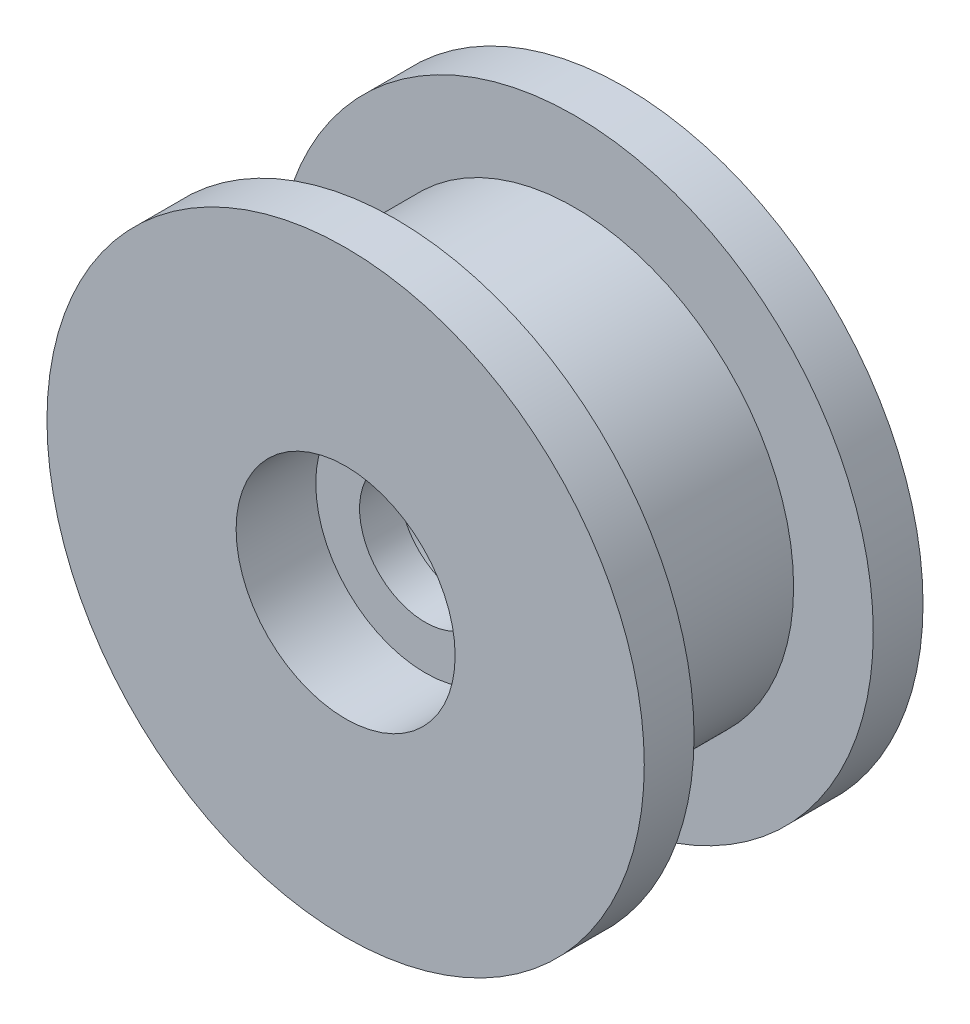
SolidWorks part; units mm, degrees
ref_plane "Front Plane" through (0, 0, 0) normal (0, 0, 1) x (1, 0, 0)
ref_plane "Top Plane" through (0, 0, 0) normal (0, 1, 0) x (1, 0, 0)
ref_plane "Right Plane" through (0, 0, 0) normal (1, 0, 0) x (0, 0, -1)
sketch "Sketch1" plane through (0, 0, 0) normal (0, 1, 0) x (1, 0, 0)
  line L0 (0, 0) -> (0, 21.2409) construction
  line L1 (1.65, 0) -> (7.5, 0)
  line L2 (7.5, 0) -> (7.5, 1.25)
  line L3 (7.5, 1.25) -> (5.5, 1.25)
  line L5 (3, 9) -> (2.75, 9)
  line L6 (2.75, 9) -> (2.75, 3)
  line L7 (2.75, 3) -> (1.65, 3)
  line L8 (1.65, 3) -> (1.65, 0)
  line L12 (3, 7) -> (3, 9)
  line L13 (3, 7) -> (7.5, 7)
  line L14 (7.5, 7) -> (7.5, 5.75)
  line L15 (7.5, 5.75) -> (5.5, 5.75)
  line L16 (5.5, 5.75) -> (5.5, 1.25)
  dimension "D1" = 3.3
  dimension "D2" = 11
  dimension "D3" = 15
  dimension "D4" = 5.5
  dimension "D5" = 9
  dimension "D6" = 2
  dimension "D7" = 6
  dimension "D8" = 15
  dimension "D9" = 3
  dimension "D10" = 4.5
revolve "Revolve1" add sketch "Sketch1" angle 360 about L0
sketch "Sketch2" plane through (0, 0, -9) normal (0, 0, -1) x (-1, 0, 0)
  circle A0 centre (0, 0) radius 3
extrude "Cut-Extrude1" cut sketch "Sketch2" against normal blind 2
sketch "Sketch3" plane through (0, 0, 0) normal (0, 0, 1) x (1, 0, 0)
  circle A0 centre (0, 0) radius 2.75
  dimension "D1" = 5.5
extrude "Cut-Extrude2" cut sketch "Sketch3" against normal blind 2
